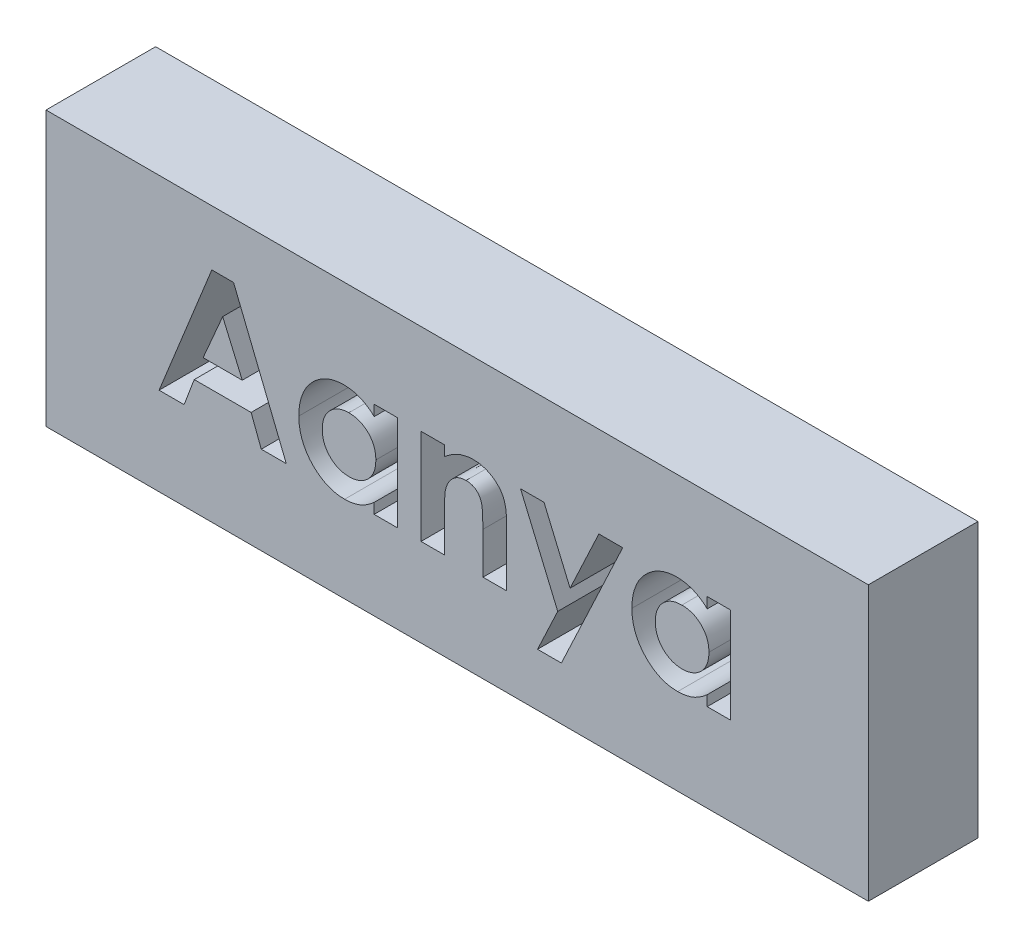
SolidWorks part; units mm, degrees
ref_plane "Front Plane" through (0, 0, 0) normal (0, 0, 1) x (1, 0, 0)
ref_plane "Top Plane" through (0, 0, 0) normal (0, 1, 0) x (1, 0, 0)
ref_plane "Right Plane" through (0, 0, 0) normal (1, 0, 0) x (0, 0, -1)
sketch "Sketch1" plane through (0, 0, 0) normal (0, 0, 1) x (1, 0, 0)
  line L0 (-8.9502, 2.9728) -> (-8.1574, 2.9728)
  line L1 (-15, -5) -> (15, -5)
  line L2 (-15, -5) -> (-15, 5)
  line L3 (-15, 5) -> (15, 5)
  line L4 (15, -5) -> (15, 5)
  line L5 (-14.4279, -5.432) -> (15.5721, 4.568) construction
  line L6 (-14.4279, 4.568) -> (15.5721, -5.432) construction
  line L7 (-8.1574, 2.9728) -> (-6.2341, -1.7897)
  line L8 (-6.2341, -1.7897) -> (-7.1471, -1.7897)
  line L9 (-7.1471, -1.7897) -> (-7.5173, -0.8128)
  line L10 (-7.5173, -0.8128) -> (-9.5923, -0.8128)
  line L11 (-9.5923, -0.8128) -> (-9.9624, -1.7897)
  line L12 (-9.9624, -1.7897) -> (-10.8745, -1.7897)
  line L13 (-10.8745, -1.7897) -> (-8.9502, 2.9728)
  line L14 (-8.5543, 1.6954) -> (-9.2679, 0.042)
  line L15 (-9.2679, 0.042) -> (-7.8407, 0.042)
  line L16 (-7.8407, 0.042) -> (-8.5543, 1.6954)
  line L17 (-3.0286, 1.6906) -> (-2.1738, 1.6906)
  line L18 (-2.1738, 1.6906) -> (-2.1738, -1.7897)
  line L19 (-2.1738, -1.7897) -> (-3.0286, -1.7897)
  line L20 (-3.0286, -1.7897) -> (-3.0286, -1.41)
  line L21 (-3.0286, 1.2985) -> (-3.0286, 1.6906)
  line L22 (-1.319, 1.6906) -> (-0.4642, 1.6906)
  line L23 (-0.4642, 1.6906) -> (-0.4642, 1.3223)
  line L24 (1.795, 0.4923) -> (1.795, -1.7897)
  line L25 (1.795, -1.7897) -> (0.9402, -1.7897)
  line L26 (0.9402, -1.7897) -> (0.9402, -0.2785)
  line L27 (-0.4642, -0.4045) -> (-0.4642, -1.7897)
  line L28 (-0.4642, -1.7897) -> (-1.319, -1.7897)
  line L29 (-1.319, -1.7897) -> (-1.319, 1.6906)
  line L30 (2.3121, 1.6906) -> (3.1678, 1.6906)
  line L31 (3.1678, 1.6906) -> (4.118, -0.5485)
  line L32 (4.118, -0.5485) -> (5.1694, 1.6906)
  line L33 (5.1694, 1.6906) -> (6.0385, 1.6906)
  line L34 (6.0385, 1.6906) -> (3.8013, -3.0719)
  line L35 (3.8013, -3.0719) -> (2.9322, -3.0719)
  line L36 (2.9322, -3.0719) -> (3.6677, -1.5064)
  line L37 (3.6677, -1.5064) -> (2.3121, 1.6906)
  line L38 (9.1219, 1.6906) -> (9.9767, 1.6906)
  line L39 (9.9767, 1.6906) -> (9.9767, -1.7897)
  line L40 (9.9767, -1.7897) -> (9.1219, -1.7897)
  line L41 (9.1219, -1.7897) -> (9.1219, -1.41)
  line L42 (9.1219, 1.2985) -> (9.1219, 1.6906)
  spline S0 degree 3 poles (-3.0286, -1.41) (-3.1094, -1.483) (-3.2341, -1.5832) (-3.4126, -1.6885) (-3.5435, -1.7497) (-3.6774, -1.7948) (-3.8637, -1.8392) (-4.0089, -1.8501) (-4.1066, -1.8508) knots 0 0 0 0 0.273944 0.399987 0.519719 0.636176 0.754371 1 1 1 1
  spline S1 degree 3 poles (-4.1066, -1.8508) (-4.2168, -1.8519) (-4.3802, -1.8351) (-4.5903, -1.7809) (-4.7407, -1.7245) (-4.8852, -1.6512) (-5.0248, -1.5632) (-5.1571, -1.4573) (-5.2833, -1.338) (-5.3989, -1.2068) (-5.4999, -1.0656) (-5.585, -0.9162) (-5.6548, -0.7592) (-5.7096, -0.5947) (-5.7628, -0.3613) (-5.7758, -0.1791) (-5.7762, -0.0562) knots 0 0 0 0 0.121092 0.179634 0.238304 0.297437 0.357507 0.419513 0.4836 0.548295 0.611487 0.674313 0.737107 0.80016 0.864737 1 1 1 1
  spline S2 degree 3 poles (-5.7762, -0.0562) (-5.7752, 0.0703) (-5.7638, 0.2579) (-5.7114, 0.4979) (-5.6591, 0.6657) (-5.5918, 0.8245) (-5.5097, 0.9747) (-5.4119, 1.1158) (-5.2992, 1.2454) (-5.1775, 1.3642) (-5.0473, 1.4677) (-4.9107, 1.5555) (-4.7674, 1.6273) (-4.6175, 1.6827) (-4.4074, 1.7376) (-4.243, 1.7518) (-4.1324, 1.7516) knots 0 0 0 0 0.139309 0.205474 0.269598 0.332253 0.39483 0.457376 0.520582 0.583374 0.644082 0.70304 0.761664 0.819844 0.878346 1 1 1 1
  spline S3 degree 3 poles (-4.1324, 1.7516) (-4.0296, 1.7528) (-3.8772, 1.7376) (-3.6803, 1.6902) (-3.5392, 1.6403) (-3.4023, 1.5772) (-3.2258, 1.4705) (-3.1038, 1.3723) (-3.0286, 1.2985) knots 0 0 0 0 0.251537 0.373434 0.495667 0.61768 0.742091 1 1 1 1
  spline S4 degree 3 poles (-3.953, 0.9579) (-4.0197, 0.9568) (-4.1188, 0.9503) (-4.2459, 0.9208) (-4.3347, 0.8887) (-4.4198, 0.8496) (-4.4999, 0.8007) (-4.5757, 0.7429) (-4.6467, 0.6775) (-4.7115, 0.6057) (-4.7673, 0.5273) (-4.8148, 0.4445) (-4.8549, 0.357) (-4.8836, 0.2638) (-4.9145, 0.1313) (-4.9199, 0.0272) (-4.9214, -0.0429) knots 0 0 0 0 0.128421 0.189996 0.250359 0.309744 0.369856 0.430537 0.492876 0.555257 0.616197 0.677577 0.738631 0.800922 0.864882 1 1 1 1
  spline S5 degree 3 poles (-4.9214, -0.0429) (-4.9201, -0.1136) (-4.914, -0.2184) (-4.8842, -0.3528) (-4.8522, -0.4464) (-4.8132, -0.5357) (-4.7656, -0.6204) (-4.7072, -0.6988) (-4.6424, -0.7729) (-4.5699, -0.839) (-4.4937, -0.8978) (-4.4127, -0.9469) (-4.3277, -0.9866) (-4.2392, -1.019) (-4.1133, -1.0481) (-4.0154, -1.0567) (-3.9492, -1.057) knots 0 0 0 0 0.135365 0.199461 0.262264 0.323991 0.385461 0.447171 0.510418 0.573171 0.634271 0.693954 0.753723 0.813084 0.873629 1 1 1 1
  spline S6 degree 3 poles (-3.9492, -1.057) (-3.8813, -1.0559) (-3.7806, -1.0495) (-3.6516, -1.0199) (-3.5616, -0.9876) (-3.4753, -0.9489) (-3.3935, -0.9009) (-3.3171, -0.8432) (-3.2457, -0.7772) (-3.1802, -0.7048) (-3.1236, -0.6254) (-3.0743, -0.5416) (-3.0356, -0.4513) (-3.0048, -0.3561) (-2.9747, -0.2194) (-2.9688, -0.1123) (-2.9675, -0.04) knots 0 0 0 0 0.128662 0.18979 0.249707 0.309189 0.3685 0.428644 0.489937 0.552121 0.612878 0.67405 0.735729 0.798305 0.862953 1 1 1 1
  spline S7 degree 3 poles (-2.9675, -0.04) (-2.9688, 0.0307) (-2.9747, 0.1356) (-3.005, 0.2697) (-3.0351, 0.3632) (-3.0746, 0.4513) (-3.1239, 0.5331) (-3.1799, 0.6115) (-3.2461, 0.6819) (-3.3171, 0.7474) (-3.3947, 0.8033) (-3.4763, 0.8516) (-3.5625, 0.8912) (-3.654, 0.9202) (-3.7834, 0.9508) (-3.8849, 0.9567) (-3.953, 0.9579) knots 0 0 0 0 0.135096 0.199063 0.261548 0.322044 0.382646 0.443385 0.505155 0.566516 0.627254 0.687026 0.74697 0.807539 0.869733 1 1 1 1
  spline S8 degree 3 poles (-0.4642, 1.3223) (-0.3723, 1.3964) (-0.2344, 1.4949) (-0.0468, 1.6008) (0.082, 1.6584) (0.2082, 1.6997) (0.3754, 1.7396) (0.5036, 1.7522) (0.5891, 1.7516) knots 0 0 0 0 0.304989 0.436681 0.556242 0.668759 0.779379 1 1 1 1
  spline S9 degree 3 poles (0.5891, 1.7516) (0.6739, 1.7507) (0.8004, 1.7425) (0.9621, 1.7029) (1.0774, 1.6641) (1.1873, 1.6128) (1.3298, 1.5311) (1.4247, 1.4502) (1.4849, 1.3929) knots 0 0 0 0 0.257369 0.381171 0.503299 0.625248 0.747811 1 1 1 1
  spline S10 degree 3 poles (1.4849, 1.3929) (1.5366, 1.3416) (1.6053, 1.2546) (1.6763, 1.1234) (1.7205, 1.0151) (1.7531, 0.8967) (1.7877, 0.7227) (1.7944, 0.5857) (1.795, 0.4923) knots 0 0 0 0 0.22321 0.337546 0.456528 0.581244 0.713405 1 1 1 1
  spline S11 degree 3 poles (0.9402, -0.2785) (0.9399, -0.1841) (0.9391, -0.0488) (0.9318, 0.1225) (0.9271, 0.2317) (0.9178, 0.3277) (0.9094, 0.411) (0.8965, 0.4809) (0.8798, 0.5561) (0.8506, 0.6365) (0.8052, 0.7214) (0.7476, 0.7934) (0.6803, 0.8532) (0.6031, 0.9005) (0.4852, 0.9464) (0.3885, 0.9582) (0.3229, 0.9579) knots 0 0 0 0 0.179518 0.256937 0.32593 0.387213 0.440139 0.484952 0.522188 0.586422 0.647004 0.704202 0.760716 0.817414 0.875213 1 1 1 1
  spline S12 degree 3 poles (0.3229, 0.9579) (0.2364, 0.957) (0.1061, 0.938) (-0.0494, 0.8615) (-0.1536, 0.7834) (-0.2455, 0.6869) (-0.35, 0.5288) (-0.4008, 0.3921) (-0.4241, 0.2958) knots 0 0 0 0 0.240658 0.35739 0.477137 0.600009 0.725225 1 1 1 1
  spline S13 degree 3 poles (-0.4241, 0.2958) (-0.4331, 0.2614) (-0.4397, 0.2029) (-0.4502, 0.1176) (-0.4536, 0.036) (-0.4593, -0.0574) (-0.4623, -0.2057) (-0.4641, -0.3227) (-0.4642, -0.4045) knots 0 0 0 0 0.151476 0.251213 0.366854 0.500124 0.650932 1 1 1 1
  spline S14 degree 3 poles (9.1219, -1.41) (9.041, -1.483) (8.9164, -1.5832) (8.7379, -1.6885) (8.607, -1.7497) (8.4731, -1.7948) (8.2868, -1.8392) (8.1415, -1.8501) (8.0438, -1.8508) knots 0 0 0 0 0.273944 0.399987 0.519719 0.636176 0.754371 1 1 1 1
  spline S15 degree 3 poles (8.0438, -1.8508) (7.9337, -1.8519) (7.7703, -1.8351) (7.5602, -1.7809) (7.4097, -1.7245) (7.2653, -1.6512) (7.1257, -1.5632) (6.9933, -1.4573) (6.8671, -1.338) (6.7516, -1.2068) (6.6506, -1.0656) (6.5654, -0.9162) (6.4957, -0.7592) (6.4408, -0.5947) (6.3877, -0.3613) (6.3747, -0.1791) (6.3743, -0.0562) knots 0 0 0 0 0.121092 0.179634 0.238304 0.297437 0.357507 0.419513 0.4836 0.548295 0.611487 0.674313 0.737107 0.80016 0.864737 1 1 1 1
  spline S16 degree 3 poles (6.3743, -0.0562) (6.3753, 0.0703) (6.3867, 0.2579) (6.439, 0.4979) (6.4914, 0.6657) (6.5587, 0.8245) (6.6407, 0.9747) (6.7385, 1.1158) (6.8513, 1.2454) (6.973, 1.3642) (7.1032, 1.4677) (7.2398, 1.5555) (7.3831, 1.6273) (7.5329, 1.6827) (7.7431, 1.7376) (7.9075, 1.7518) (8.0181, 1.7516) knots 0 0 0 0 0.139309 0.205474 0.269598 0.332253 0.39483 0.457376 0.520582 0.583374 0.644082 0.70304 0.761664 0.819844 0.878346 1 1 1 1
  spline S17 degree 3 poles (8.0181, 1.7516) (8.1209, 1.7528) (8.2732, 1.7376) (8.4702, 1.6902) (8.6113, 1.6403) (8.7482, 1.5772) (8.9247, 1.4705) (9.0467, 1.3723) (9.1219, 1.2985) knots 0 0 0 0 0.251537 0.373434 0.495667 0.61768 0.742091 1 1 1 1
  spline S18 degree 3 poles (8.1974, 0.9579) (8.1308, 0.9568) (8.0317, 0.9503) (7.9046, 0.9208) (7.8158, 0.8887) (7.7307, 0.8496) (7.6506, 0.8007) (7.5748, 0.7429) (7.5037, 0.6775) (7.439, 0.6057) (7.3832, 0.5273) (7.3357, 0.4445) (7.2956, 0.357) (7.2669, 0.2638) (7.236, 0.1313) (7.2306, 0.0272) (7.2291, -0.0429) knots 0 0 0 0 0.128421 0.189996 0.250359 0.309744 0.369856 0.430537 0.492876 0.555257 0.616197 0.677577 0.738631 0.800922 0.864882 1 1 1 1
  spline S19 degree 3 poles (7.2291, -0.0429) (7.2304, -0.1136) (7.2365, -0.2184) (7.2663, -0.3528) (7.2982, -0.4464) (7.3373, -0.5357) (7.3849, -0.6204) (7.4433, -0.6988) (7.5081, -0.7729) (7.5806, -0.839) (7.6568, -0.8978) (7.7378, -0.9469) (7.8227, -0.9866) (7.9113, -1.019) (8.0372, -1.0481) (8.1351, -1.0567) (8.2013, -1.057) knots 0 0 0 0 0.135365 0.199461 0.262264 0.323991 0.385461 0.447171 0.510418 0.573171 0.634271 0.693954 0.753723 0.813084 0.873629 1 1 1 1
  spline S20 degree 3 poles (8.2013, -1.057) (8.2692, -1.0559) (8.3699, -1.0495) (8.4988, -1.0199) (8.5888, -0.9876) (8.6751, -0.9489) (8.7569, -0.9009) (8.8334, -0.8432) (8.9048, -0.7772) (8.9703, -0.7048) (9.0268, -0.6254) (9.0761, -0.5416) (9.1149, -0.4513) (9.1457, -0.3561) (9.1758, -0.2194) (9.1817, -0.1123) (9.183, -0.04) knots 0 0 0 0 0.128662 0.18979 0.249707 0.309189 0.3685 0.428644 0.489937 0.552121 0.612878 0.67405 0.735729 0.798305 0.862953 1 1 1 1
  spline S21 degree 3 poles (9.183, -0.04) (9.1817, 0.0307) (9.1758, 0.1356) (9.1455, 0.2697) (9.1153, 0.3632) (9.0759, 0.4513) (9.0265, 0.5331) (8.9706, 0.6115) (8.9044, 0.6819) (8.8333, 0.7474) (8.7558, 0.8033) (8.6742, 0.8516) (8.588, 0.8912) (8.4965, 0.9202) (8.3671, 0.9508) (8.2656, 0.9567) (8.1974, 0.9579) knots 0 0 0 0 0.135096 0.199063 0.261548 0.322044 0.382646 0.443385 0.505155 0.566516 0.627254 0.687026 0.74697 0.807539 0.869733 1 1 1 1
  point P0 (0.5721, -0.432)
  dimension "D1" = 10
  dimension "D2" = 30
extrude "Boss-Extrude1" add sketch "Sketch1" along normal blind 4 contours L1 L4 L3 L2 L12 L13 L0 L7 L8 L9 L10 L11 L36 L37 L30 L31 L32 L33 L34 L35 S2 S3 L21 L17 L18 L19 L20 S0 S1 S12 S13 L27 L28 L29 L22 L23 S8 S9 S10 L24 L25 L26 S11 S16 S17 L42 | S6 S7 S4 S5 | L15 L16 L14 | S20 S21 S18 S19
